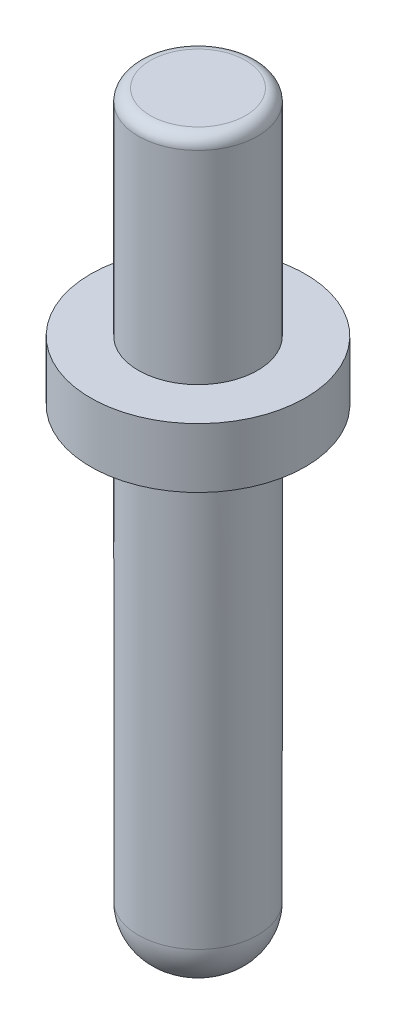
SolidWorks part; units mm, degrees
ref_plane "前视基准面" through (0, 0, 0) normal (0, 0, 1) x (1, 0, 0)
ref_plane "上视基准面" through (0, 0, 0) normal (0, 1, 0) x (1, 0, 0)
ref_plane "右视基准面" through (0, 0, 0) normal (1, 0, 0) x (0, 0, -1)
sketch "草图1" plane through (0, 0, 0) normal (0, 0, 1) x (1, 0, 0)
  line L0 (0, 13.6872) -> (0, -9.0872) construction
  line L1 (0, -4) -> (-0.5, -4)
  line L2 (-0.5, -4) -> (-0.5, 0)
  line L3 (-0.5, 0) -> (-0.9, 0)
  line L4 (-0.9, 0) -> (-0.9, 0.5)
  line L5 (-0.9, 0.5) -> (-0.5, 0.5)
  line L6 (-0.5, 0.5) -> (-0.5, 2.3)
  line L7 (-0.5, 2.3) -> (0, 2.3)
  line L8 (0, -4) -> (0, 2.3)
  line L12 (5.0295, 0) -> (-9.301, 0) construction
  point P23 (-0.9, 0.25)
  dimension "D1" = 6.3
  dimension "D2" = 0.5
  dimension "D3" = 0.5
  dimension "D4" = 1.8
  dimension "D5" = 0.5
  dimension "D6" = 0.9
revolve "旋转1" add sketch "草图1" angle 360 about L0
fillet "圆角1" radius 0.1 1 edges at (-0.5, 2.3, 0)
fillet "圆角2" radius 0.4 1 edges at (-0.5, -4, 0)
